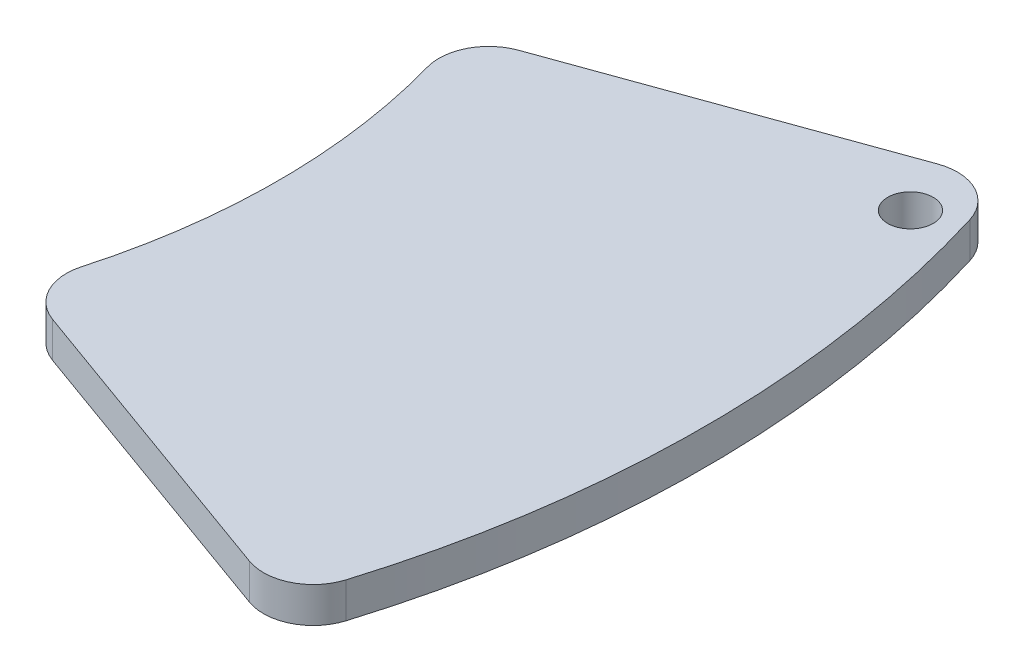
SolidWorks part; units mm, degrees
ref_plane "Front Plane" through (0, 0, 0) normal (0, 0, 1) x (1, 0, 0)
ref_plane "Top Plane" through (0, 0, 0) normal (0, 1, 0) x (1, 0, 0)
ref_plane "Right Plane" through (0, 0, 0) normal (1, 0, 0) x (0, 0, -1)
sketch "Sketch1" plane through (0, 0, 0) normal (0, 1, 0) x (1, 0, 0)
  line L0 (53.7646, 19.3776) -> (89.6076, 32.2961)
  line L1 (53.7646, -19.3776) -> (89.6076, -32.2961)
  arc A0 (89.6076, -32.2961) -> (89.6076, 32.2961) centre (0, 0) ccw
  arc A1 (53.7646, -19.3776) -> (53.7646, 19.3776) centre (0, 0) ccw
  point P1 (56.7853, 41.4787)
  point P3 (57.15, 0)
  point P8 (89.6076, -32.2961)
  dimension "D1" = 190.5
  dimension "D2" = 114.3
extrude "Boss-Extrude1" add sketch "Sketch1" along normal blind 3.175
sketch "Sketch2" plane through (0, 3.175, 0) normal (0, 1, 0) x (1, 0, 0)
  circle A0 centre (87.7026, 25.9461) radius 2.032
  point P2 (87.7212, 28.4609)
  point P3 (0, 0)
  point P7 (84.0917, 35.4981)
  point P8 (88.0266, 28.4927)
  dimension "D1" = 4.064
  dimension "D2" = 6.35
  dimension "D3" = 1.905
extrude "Cut-Extrude1" cut sketch "Sketch2" against normal through all
fillet "Fillet1" radius 4.445 4 edges at (53.7646, 1.5875, 19.3776) (53.7646, 1.5875, -19.3776) (89.6076, 1.5875, -32.2961) (89.6076, 1.5875, 32.2961)
